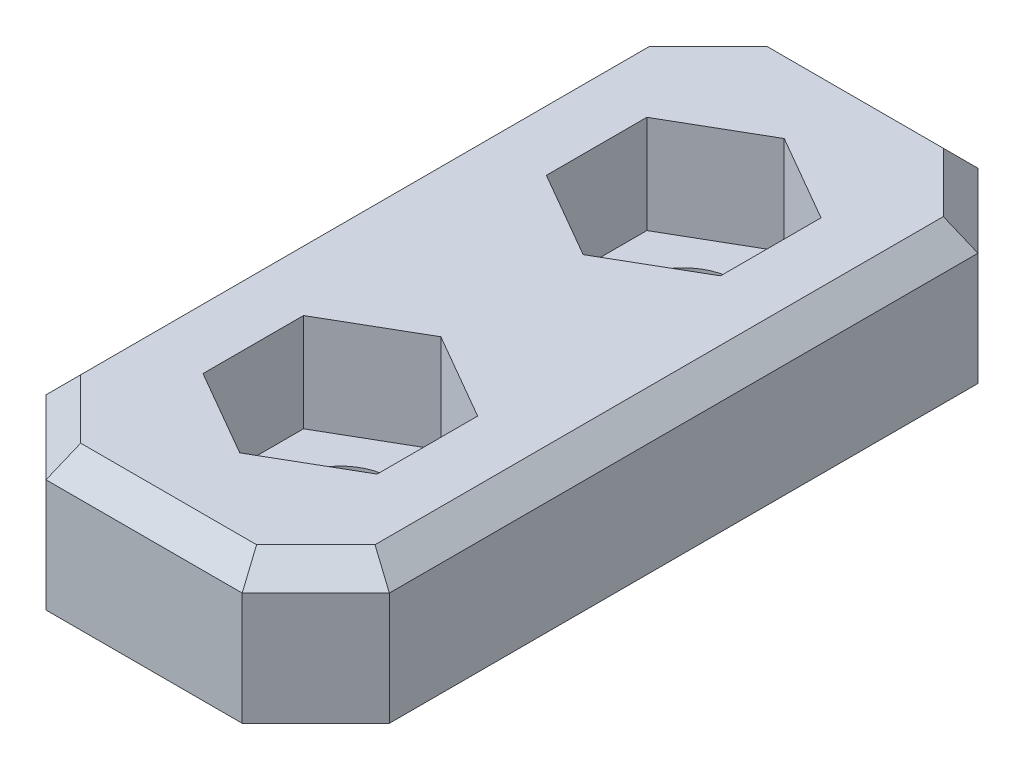
SolidWorks part; units mm, degrees
ref_plane "Front Plane" through (0, 0, 0) normal (0, 0, 1) x (1, 0, 0)
ref_plane "Top Plane" through (0, 0, 0) normal (0, 1, 0) x (1, 0, 0)
ref_plane "Right Plane" through (0, 0, 0) normal (1, 0, 0) x (0, 0, -1)
sketch "Sketch1" plane through (0, 0, 0) normal (0, 1, 0) x (1, 0, 0)
  line L0 (7, 30) -> (7, 0) construction
  line L1 (0, 0) -> (14, 0)
  line L2 (0, 0) -> (0, 30)
  line L3 (0, 30) -> (14, 30)
  line L4 (14, 0) -> (14, 30)
  circle A0 centre (7, 22) radius 2.1
  circle A1 centre (7, 8) radius 2.1
  dimension "D3" = 14
  dimension "D4" = 8
  dimension "D1" = 30
  dimension "D2" = 14
extrude "Boss-Extrude1" add sketch "Sketch1" along normal blind 5.6
sketch "Sketch2" plane through (0, 5.6, 0) normal (0, 1, 0) x (1, 0, 0)
  line L0 (14, 0) -> (14, 30) construction
  line L1 (10.55, 24.0496) -> (7, 26.0992)
  line L2 (7, 26.0992) -> (3.45, 24.0496)
  line L3 (3.45, 24.0496) -> (3.45, 19.9504)
  line L4 (3.45, 19.9504) -> (7, 17.9008)
  line L5 (7, 17.9008) -> (10.55, 19.9504)
  line L6 (10.55, 19.9504) -> (10.55, 24.0496)
  line L7 (10.55, 10.0496) -> (7, 12.0992)
  line L8 (7, 12.0992) -> (3.45, 10.0496)
  line L9 (3.45, 10.0496) -> (3.45, 5.9504)
  line L10 (3.45, 5.9504) -> (7, 3.9008)
  line L11 (7, 3.9008) -> (10.55, 5.9504)
  line L12 (10.55, 5.9504) -> (10.55, 10.0496)
  circle A0 centre (7, 22) radius 3.55 construction
  circle A1 centre (7, 8) radius 3.55 construction
  dimension "D1" = 7.1
  dimension "D2" = 0
  dimension "D3" = 7.1
  dimension "D4" = 0
extrude "Cut-Extrude1" cut sketch "Sketch2" against normal blind 4
chamfer "Chamfer1" distance 3 angle 45 4 edges at (14, 2.8, -30) (0, 2.8, -30) (0, 2.8, 0) (14, 2.8, 0)
chamfer "Chamfer2" distance 1 angle 45 8 edges at (12.5, 5.6, -1.5) (7, 5.6, 0) (1.5, 5.6, -1.5) (0, 5.6, -15) (1.5, 5.6, -28.5) (7, 5.6, -30) (12.5, 5.6, -28.5) (14, 5.6, -15)
